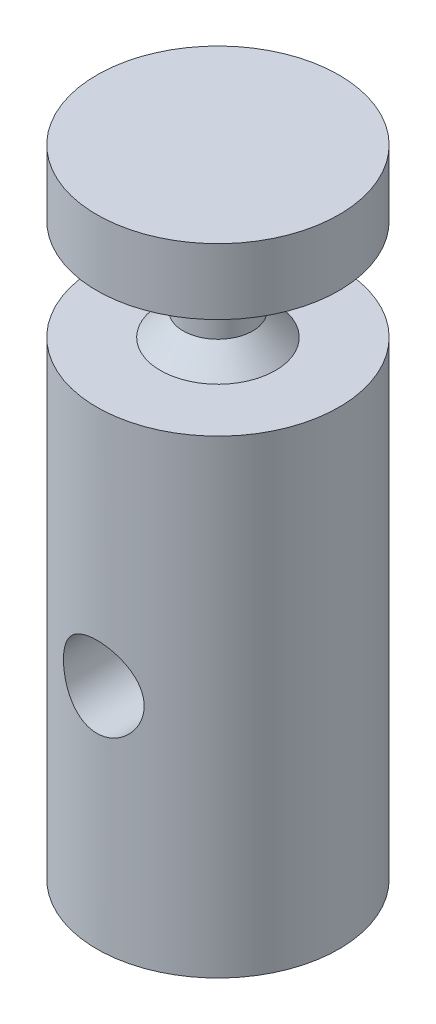
SolidWorks part; units mm, degrees
material "AISI 316 Barra de acero inoxidable recocido (SS)"
ref_plane "Alzado" through (0, 0, 0) normal (0, 0, 1) x (1, 0, 0)
ref_plane "Planta" through (0, 0, 0) normal (0, 1, 0) x (1, 0, 0)
ref_plane "Vista lateral" through (0, 0, 0) normal (1, 0, 0) x (0, 0, -1)
sketch "Croquis1" plane through (0, 0, 0) normal (0, 0, 1) x (1, 0, 0)
  line L0 (0, 0) -> (0, 41.1951) construction
  line L1 (0, 0) -> (-9.525, 0)
  line L2 (-9.525, 36.9228) -> (-9.525, 22.6347)
  line L3 (-9.525, 50.038) -> (-9.525, 44.8627)
  line L4 (-9.525, 44.8627) -> (-4.525, 44.8627)
  line L5 (-9.525, 50.038) -> (0, 50.038)
  line L6 (0, 50.038) -> (0, 0)
  line L7 (-9.525, 2) -> (-9.525, 0)
  line L8 (-9.525, 22.6347) -> (-9.525, 2)
  line L9 (-4.525, 44.8627) -> (-2.73, 43.0678)
  line L10 (-2.73, 43.0678) -> (-2.73, 38.7178)
  line L11 (-2.73, 38.7178) -> (-4.525, 36.9228)
  line L12 (-4.525, 36.9228) -> (-9.525, 36.9228)
  dimension "D7" = 4.35
  dimension "D1" = 50.038
  dimension "D2" = 36.9228
  dimension "D3" = 2
  dimension "D4" = 14.288
  dimension "D5" = 19.05
  dimension "D6" = 5.1752
  dimension "D8" = 5
revolve "Revolución1" add sketch "Croquis1" angle 360 about L0
hole_wizard "Diámetro de taladro 1/4 (0.25)1" positions "Croquis3D1" profile "Croquis2" hole size "1/4" standard "Ansi Inch" end condition through all
sketch3d "Croquis3D1"
  line L0 (0, 0, 0) -> (0, 17.875, 0) construction
  line L2 (0, 17.875, 0) -> (0, 17.875, 9.525)
  point P0 (0, 17.875, 9.525)
sketch "Croquis2" plane through (0, 17.875, 9.525) normal (1, 0, 0) x (0, -1, 0)
  line L0 (0, 0) -> (0, 19.05)
  line L1 (0, 19.05) -> (3.175, 19.05)
  line L2 (3.175, 19.05) -> (3.175, 0)
  line L5 (3.175, 0) -> (0, 0)
  line L11 (0, -6.35) -> (0, 107.95) construction
  dimension "Diámetro de taladro hasta el siguiente" = 6.35
  dimension "Profundidad de taladro hasta el siguiente" = 19.05
